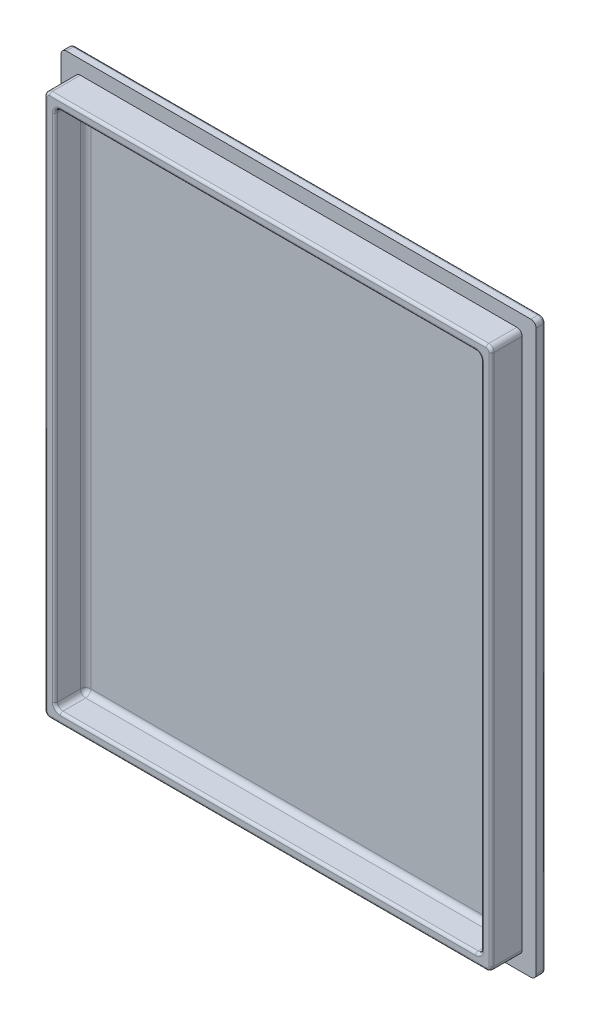
SolidWorks part; units mm, degrees
ref_plane "Front Plane" through (0, 0, 0) normal (0, 0, 1) x (1, 0, 0)
ref_plane "Top Plane" through (0, 0, 0) normal (0, 1, 0) x (1, 0, 0)
ref_plane "Right Plane" through (0, 0, 0) normal (1, 0, 0) x (0, 0, -1)
sketch "Sketch1" plane through (0, 0, 0) normal (0, 0, 1) x (1, 0, 0)
  line L1 (-45, 54) -> (45, 54)
  line L2 (-45, 54) -> (-45, -54)
  line L3 (-45, -54) -> (45, -54)
  line L4 (45, 54) -> (45, -54)
  line L5 (-45, 54) -> (45, -54) construction
  line L6 (-45, -54) -> (45, 54) construction
  point P0 (0, 0)
  dimension "D1" = 108
  dimension "D2" = 90
extrude "Boss-Extrude1" add sketch "Sketch1" along normal blind 1.8
sketch "Sketch2" plane through (0, 0, 1.8) normal (0, 0, 1) x (1, 0, 0)
  line L0 (45, 54) -> (-45, 54) construction
  line L1 (42.35, -51.35) -> (-42.35, -51.35)
  line L2 (42.35, -51.35) -> (42.35, 51.35)
  line L3 (42.35, 51.35) -> (-42.35, 51.35)
  line L4 (-42.35, -51.35) -> (-42.35, 51.35)
  line L5 (42.35, -51.35) -> (-42.35, 51.35) construction
  line L6 (42.35, 51.35) -> (-42.35, -51.35) construction
  line L7 (45, -54) -> (45, 54) construction
  line L9 (40.35, -49.35) -> (-40.35, -49.35)
  line L10 (40.35, -49.35) -> (40.35, 49.35)
  line L11 (40.35, 49.35) -> (-40.35, 49.35)
  line L12 (-40.35, -49.35) -> (-40.35, 49.35)
  line L13 (40.35, -49.35) -> (-40.35, 49.35) construction
  line L14 (40.35, 49.35) -> (-40.35, -49.35) construction
  point P0 (0, 0)
  point P10 (0, 0)
  dimension "D1" = 2.65
  dimension "D2" = 2.65
  dimension "D3" = 2
  dimension "D4" = 2
extrude "Boss-Extrude2" add sketch "Sketch2" along normal blind 5.8
fillet "Fillet1" radius 1 16 edges at (-45, -54, 0.9) (-45, 54, 0.9) (45, -54, 0.9) (40.35, -49.35, 4.7) (40.35, 49.35, 4.7) (-40.35, 49.35, 4.7) (-40.35, -49.35, 4.7) (-42.35, 51.35, 4.7) (42.35, -51.35, 4.7) (-42.35, -51.35, 4.7) (42.35, 51.35, 4.7) (45, 54, 0.9) (0, 49.35, 1.8) (40.35, 0, 1.8) (0, -49.35, 1.8) (-40.35, 0, 1.8)
fillet "Fillet2" radius 0.5 24 edges at (44.7071, -53.7071, 0) (45, 0, 0) (44.7071, 53.7071, 0) (0, 54, 0) (-44.7071, 53.7071, 0) (-45, 0, 0) (-44.7071, -53.7071, 0) (0, -54, 0) (40.0571, -49.0571, 7.6) (40.35, 0, 7.6) (40.0571, 49.0571, 7.6) (0, 49.35, 7.6) (-40.0571, 49.0571, 7.6) (-40.35, 0, 7.6) (-40.0571, -49.0571, 7.6) (0, -49.35, 7.6) (42.0571, 51.0571, 7.6) (42.35, 0, 7.6) (42.0571, -51.0571, 7.6) (0, -51.35, 7.6) (-42.0571, -51.0571, 7.6) (-42.35, 0, 7.6) (-42.0571, 51.0571, 7.6) (0, 51.35, 7.6)
